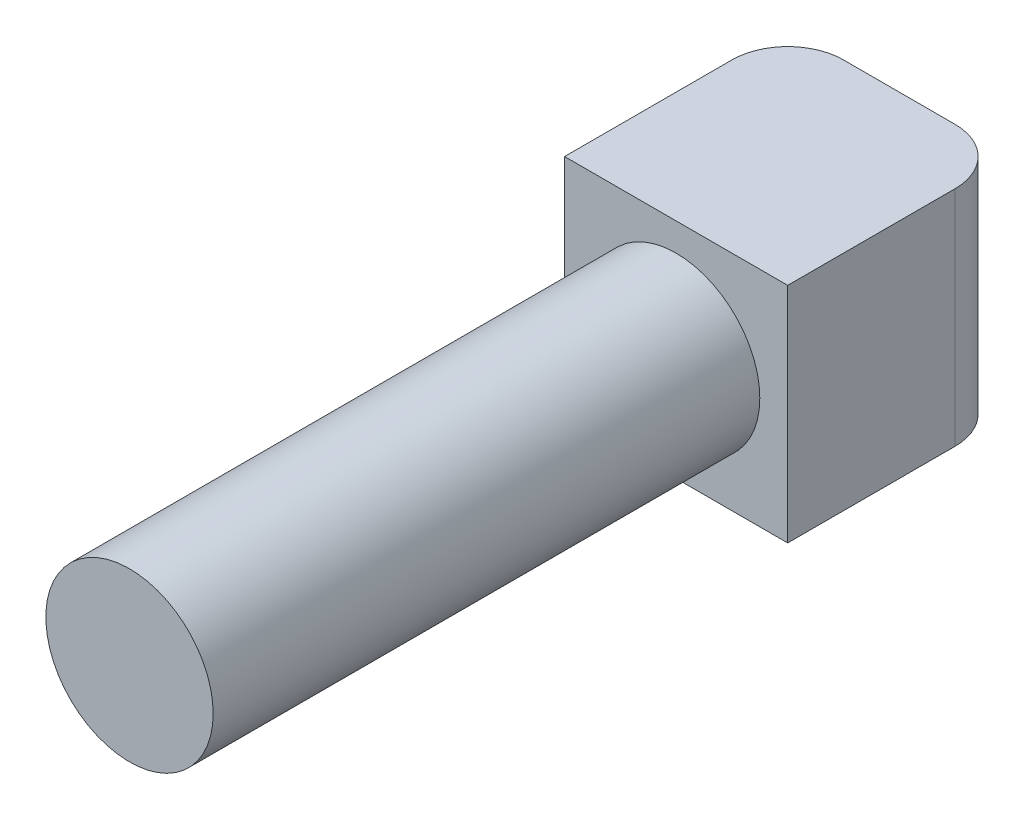
SolidWorks part; units mm, degrees
ref_plane "Front Plane" through (0, 0, 0) normal (0, 0, 1) x (1, 0, 0)
ref_plane "Top Plane" through (0, 0, 0) normal (0, 1, 0) x (1, 0, 0)
ref_plane "Right Plane" through (0, 0, 0) normal (1, 0, 0) x (0, 0, -1)
sketch "Sketch2" plane through (0, 0, 0) normal (1, 0, 0) x (0, 0, -1)
  line L1 (0, 0) -> (4, 0)
  line L2 (0, 0) -> (0, 4)
  line L3 (0, 4) -> (4, 4)
  line L4 (4, 0) -> (4, 4)
  dimension "D1" = 4
  dimension "D2" = 4
extrude "Boss-Extrude1" add sketch "Sketch2" along normal blind 4
fillet "Fillet1" radius 1 2 edges at (0, 2, -4) (4, 2, -4)
sketch "Sketch3" plane through (0, 0, 0) normal (0, 0, 1) x (1, 0, 0)
  line L0 (2, 4) -> (2, 0) construction
  line L1 (4, 4) -> (0, 4) construction
  line L2 (4, 0) -> (0, 0) construction
  circle A0 centre (2, 2) radius 1.5
  dimension "D2" = 3
  dimension "D1" = 2
extrude "Boss-Extrude2" add sketch "Sketch3" along normal blind 9.8
